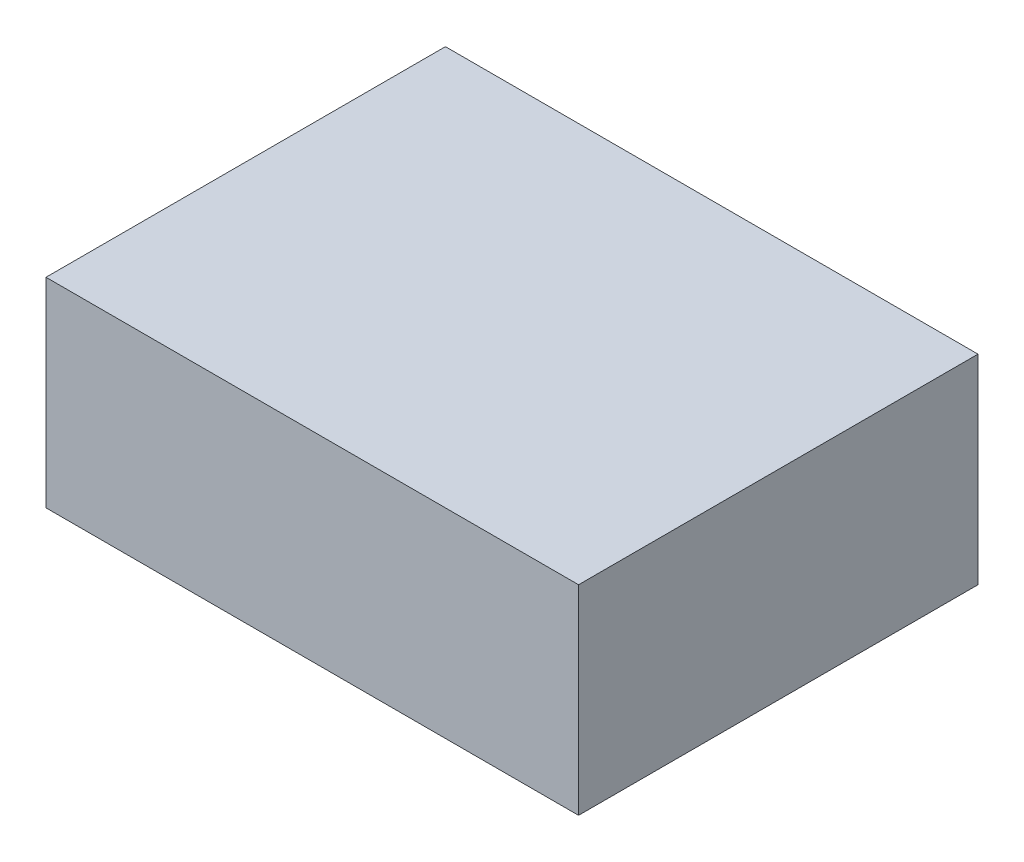
SolidWorks part; units mm, degrees
ref_plane "Front Plane" through (0, 0, 0) normal (0, 0, 1) x (1, 0, 0)
ref_plane "Top Plane" through (0, 0, 0) normal (0, 1, 0) x (1, 0, 0)
ref_plane "Right Plane" through (0, 0, 0) normal (1, 0, 0) x (0, 0, -1)
sketch "Sketch2" plane through (0, 0, 0) normal (0, 1, 0) x (1, 0, 0)
  line L1 (-101.6, 76.2) -> (101.6, 76.2)
  line L2 (-101.6, 76.2) -> (-101.6, -76.2)
  line L3 (-101.6, -76.2) -> (101.6, -76.2)
  line L4 (101.6, 76.2) -> (101.6, -76.2)
  line L5 (-101.6, 76.2) -> (101.6, -76.2) construction
  line L6 (-101.6, -76.2) -> (101.6, 76.2) construction
  point P0 (0, 0)
  dimension "D1" = 203.2
  dimension "D2" = 152.4
extrude "link2" add sketch "Sketch2" along normal blind 76.2
sketch "Sketch3" plane through (0, 0, 0) normal (0, -1, 0) x (1, 0, 0)
  circle A0 centre (50.8, 0) radius 25.4
extrude "Cut-Extrude1" cut sketch "Sketch3" against normal blind 25.4
sketch "Sketch4" plane through (-101.6, 0, 0) normal (-1, 0, 0) x (0, 0, 1)
  line L0 (-76.2, 76.2) -> (76.2, 76.2) construction
  line L1 (-63.5, 63.5) -> (63.5, 63.5)
  line L2 (-63.5, 63.5) -> (-63.5, 38.1)
  line L3 (-63.5, 38.1) -> (63.5, 38.1)
  line L4 (63.5, 63.5) -> (63.5, 38.1)
  line L5 (-63.5, 63.5) -> (63.5, 38.1) construction
  line L6 (-63.5, 38.1) -> (63.5, 63.5) construction
  line L7 (-76.2, 0) -> (76.2, 0) construction
  point P0 (0, 50.8)
  dimension "D1" = 25.4
  dimension "D2" = 127
  dimension "D3" = 12.7
  dimension "D4" = 38.1
extrude "Cut-Extrude2" cut sketch "Sketch4" against normal blind 177.8
